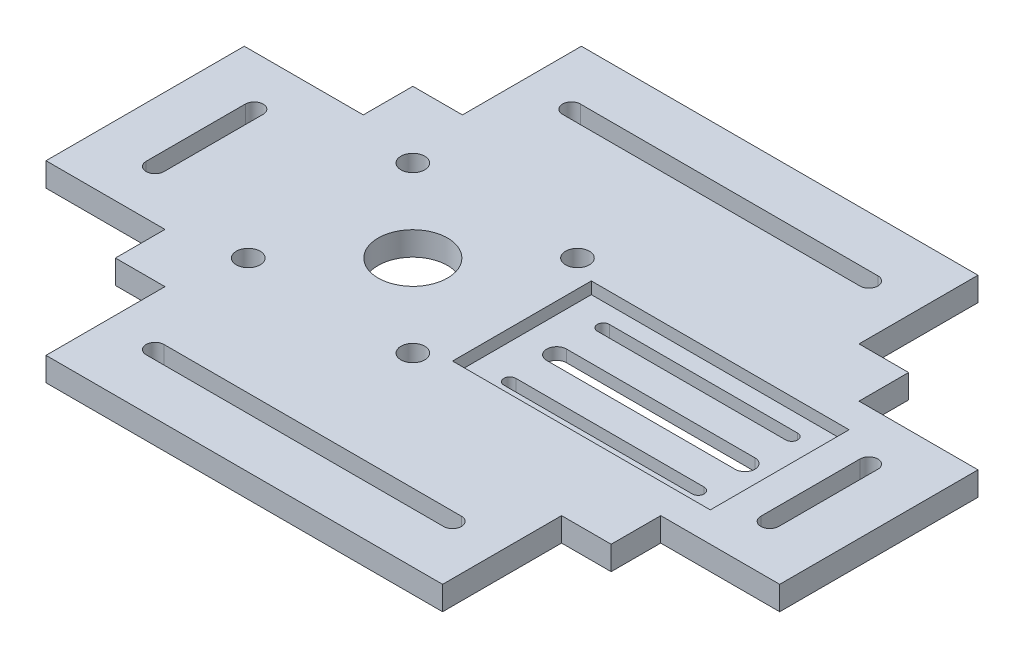
SolidWorks part; units mm, degrees
ref_plane "Front Plane" through (0, 0, 0) normal (0, 0, 1) x (1, 0, 0)
ref_plane "Top Plane" through (0, 0, 0) normal (0, 1, 0) x (1, 0, 0)
ref_plane "Right Plane" through (0, 0, 0) normal (1, 0, 0) x (0, 0, -1)
sketch "Sketch1" plane through (0, 0, 0) normal (0, 1, 0) x (1, 0, 0)
  line L1 (0, 0) -> (25, 0)
  line L2 (0, 0) -> (0, 25)
  line L3 (0, 150) -> (25, 150)
  line L4 (250, 0) -> (250, 25)
  line L5 (225, 0) -> (250, 0)
  line L6 (0, 125) -> (-60, 125)
  line L8 (0, 25) -> (-60, 25)
  line L9 (-60, 125) -> (-60, 25)
  line L10 (250, 125) -> (310, 125)
  line L12 (250, 25) -> (310, 25)
  line L13 (310, 125) -> (310, 25)
  line L15 (25, 150) -> (25, 210)
  line L16 (25, 210) -> (225, 210)
  line L17 (225, 150) -> (225, 210)
  line L19 (25, 0) -> (25, -60)
  line L20 (25, -60) -> (225, -60)
  line L21 (225, 0) -> (225, -60)
  line L22 (250, 125) -> (250, 150)
  line L23 (225, 150) -> (250, 150)
  line L24 (0, 125) -> (0, 150)
  line L25 (-30, 100) -> (-30, 50) construction
  line L26 (-25.5, 100) -> (-25.5, 50)
  line L27 (-34.5, 100) -> (-34.5, 50)
  line L28 (50, 180) -> (200, 180) construction
  line L29 (50, 184.5) -> (200, 184.5)
  line L30 (50, 175.5) -> (200, 175.5)
  line L31 (50, -30) -> (200, -30) construction
  line L32 (50, -25.5) -> (200, -25.5)
  line L33 (50, -34.5) -> (200, -34.5)
  line L34 (280, 50) -> (280, 100) construction
  line L35 (275.5, 50) -> (275.5, 100)
  line L36 (284.5, 50) -> (284.5, 100)
  line L37 (147.5, 51.43) -> (242.5, 51.43) construction
  line L38 (147.5, 54.43) -> (242.5, 54.43)
  line L39 (147.5, 48.43) -> (242.5, 48.43)
  line L40 (147.5, 98.57) -> (242.5, 98.57) construction
  line L41 (147.5, 101.57) -> (242.5, 101.57)
  line L42 (147.5, 95.57) -> (242.5, 95.57)
  line L43 (147.5, 75) -> (242.5, 75) construction
  line L44 (147.5, 80) -> (242.5, 80)
  line L45 (147.5, 70) -> (242.5, 70)
  circle A0 centre (75, 75) radius 17.5
  arc A5 (-25.5, 100) -> (-34.5, 100) centre (-30, 100) ccw
  arc A6 (-34.5, 50) -> (-25.5, 50) centre (-30, 50) ccw
  arc A7 (50, 184.5) -> (50, 175.5) centre (50, 180) ccw
  arc A8 (200, 175.5) -> (200, 184.5) centre (200, 180) ccw
  arc A9 (50, -25.5) -> (50, -34.5) centre (50, -30) ccw
  arc A10 (200, -34.5) -> (200, -25.5) centre (200, -30) ccw
  arc A11 (275.5, 50) -> (284.5, 50) centre (280, 50) ccw
  arc A12 (284.5, 100) -> (275.5, 100) centre (280, 100) ccw
  arc A13 (147.5, 54.43) -> (147.5, 48.43) centre (147.5, 51.43) ccw
  arc A14 (242.5, 48.43) -> (242.5, 54.43) centre (242.5, 51.43) ccw
  arc A15 (147.5, 101.57) -> (147.5, 95.57) centre (147.5, 98.57) ccw
  arc A16 (242.5, 95.57) -> (242.5, 101.57) centre (242.5, 98.57) ccw
  arc A17 (147.5, 80) -> (147.5, 70) centre (147.5, 75) ccw
  arc A18 (242.5, 70) -> (242.5, 80) centre (242.5, 75) ccw
  circle A19 centre (33.5, 33.5) radius 6
  circle A20 centre (116.5, 33.5) radius 6
  circle A21 centre (116.5, 116.5) radius 6
  circle A22 centre (33.5, 116.5) radius 6
  point P33 (-30, 75)
  point P38 (125, 180)
  point P45 (125, -30)
  point P52 (280, 75)
  point P61 (195, 51.43)
  point P66 (195, 98.57)
  point P73 (195, 75)
  dimension "D1" = 35
  dimension "D28" = 4.5
  dimension "D32" = 4.5
  dimension "D33" = 4.5
  dimension "D34" = 4.5
  dimension "D41" = 95
  dimension "D52" = 12
  dimension "D2" = 150
  dimension "D3" = 250
  dimension "D9" = 60
  dimension "D10" = 60
  dimension "D11" = 60
  dimension "D12" = 60
  dimension "D13" = 100
  dimension "D14" = 100
  dimension "D15" = 200
  dimension "D16" = 25
  dimension "D17" = 25
  dimension "D18" = 25
  dimension "D19" = 25
  dimension "D20" = 200
  dimension "D21" = 50
  dimension "D22" = 30
  dimension "D23" = 50
  dimension "D24" = 30
  dimension "D25" = 30
  dimension "D26" = 30
  dimension "D27" = 50
  dimension "D29" = 150
  dimension "D30" = 100
  dimension "D31" = 50
  dimension "D35" = 100
  dimension "D36" = 150
  dimension "D37" = 6
  dimension "D38" = 6
  dimension "D39" = 47.14
  dimension "D40" = 23.57
  dimension "D42" = 95
  dimension "D43" = 120
  dimension "D44" = 10
  dimension "D45" = 95
  dimension "D46" = 75
  dimension "D47" = 75
  dimension "D48" = 41.5
  dimension "D49" = 41.5
  dimension "D50" = 83
  dimension "D51" = 83
  dimension "D53" = 2
  dimension "D54" = 2
extrude "Boss-Extrude1" add sketch "Sketch1" along normal blind 12
sketch "Sketch2" plane through (0, 0, 0) normal (0, -1, 0) x (-1, 0, 0)
  line L1 (-130, 40) -> (-260, 40)
  line L2 (-130, 40) -> (-130, 110)
  line L3 (-130, 110) -> (-260, 110)
  line L4 (-260, 40) -> (-260, 110)
  circle A0 centre (-75, 75) radius 17.5 construction
  dimension "D2" = 35
  dimension "D1" = 70
  dimension "D3" = 130
  dimension "D4" = 55
extrude "Cut-Extrude1" cut sketch "Sketch2" against normal blind 6 from offset 6 offset against normal yes
